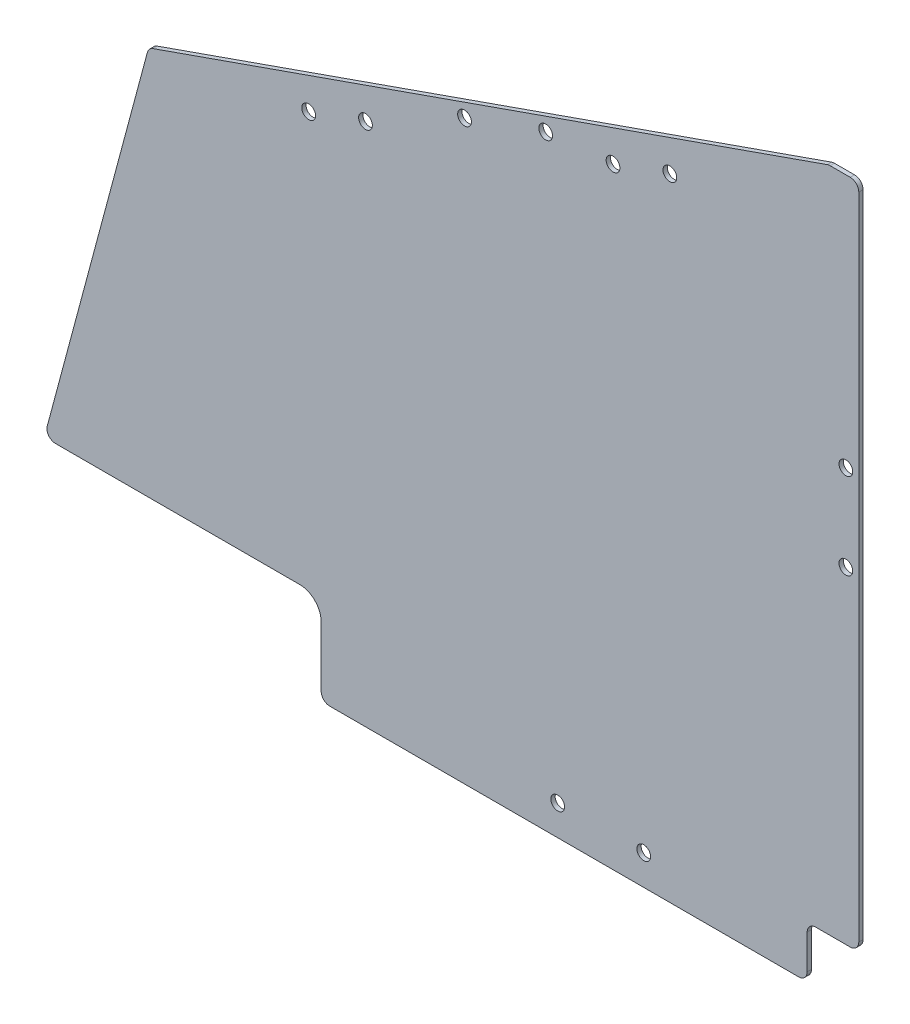
SolidWorks part; units mm, degrees
material "Thornel Mat VMA"
ref_plane "前视基准面" through (0, 0, 0) normal (0, 0, 1) x (1, 0, 0)
ref_plane "上视基准面" through (0, 0, 0) normal (0, 1, 0) x (1, 0, 0)
ref_plane "右视基准面" through (0, 0, 0) normal (1, 0, 0) x (0, 0, -1)
sketch "草图1" plane through (0, 0, 0) normal (0, 0, 1) x (1, 0, 0)
  line L1 (-95, -83.5) -> (95, -83.5)
  line L2 (-95, -83.5) -> (-95, 83.5)
  line L3 (-95, 83.5) -> (95, 83.5)
  line L4 (95, -83.5) -> (95, 83.5)
  line L5 (-95, -83.5) -> (95, 83.5) construction
  line L6 (-95, 83.5) -> (95, -83.5) construction
  point P0 (0, 0)
  dimension "D1" = 167
  dimension "D2" = 190
extrude "凸台-拉伸1" add sketch "草图1" along normal blind 1
sketch "草图2" plane through (0, 0, 0) normal (0, 0, -1) x (-1, 0, 0)
  line L0 (100, -83.5) -> (119, -83.5)
  line L1 (100, -83.5) -> (55.2525, 83.5)
  line L2 (-95, 83.5) -> (95, 83.5) construction
  line L3 (95, -83.5) -> (-95, -83.5) construction
  line L7 (119, -83.5) -> (119, 83.5)
  line L8 (119, 83.5) -> (55.2525, 83.5)
  dimension "D1" = 75
  dimension "D2" = 100
  dimension "D3" = 19
extrude "切除-拉伸1" cut sketch "草图2" against normal blind 1
sketch "草图3" plane through (0, 0, 0) normal (0, 0, -1) x (-1, 0, 0)
  line L0 (95, -83.5) -> (95, -62.5)
  line L1 (-95, -83.5) -> (-95, 83.5) construction
  line L3 (-88, 83.5) -> (55.2525, 83.5)
  line L4 (55.2525, 83.5) -> (95, -64.8397) construction
  line L5 (-88, 83.5) -> (70.1237, 28)
  line L6 (-95, 83.5) -> (55.2525, 83.5) construction
  line L7 (30, -83.5) -> (30, -62.5)
  line L8 (95, -83.5) -> (-95, -83.5) construction
  line L9 (30, -62.5) -> (95, -62.5)
  line L11 (95, -83.5) -> (30, -83.5)
  line L12 (55.2525, 83.5) -> (70.1237, 28)
  dimension "D1" = 28
  dimension "D2" = 7
  dimension "D3" = 21
  dimension "D4" = 30
extrude "切除-拉伸2" cut sketch "草图3" against normal blind 1
sketch "草图4" plane through (0, 0, 0) normal (0, 0, -1) x (-1, 0, 0)
  line L0 (0, 0) -> (-92, 0) construction
  line L1 (-92, 0) -> (-92, 4.5) construction
  line L2 (-92, 4.5) -> (-92, 24.5) construction
  line L3 (-95, -83.5) -> (-95, 83.5) construction
  circle A2 centre (-92, 4.5) radius 1.6
  circle A3 centre (-92, 24.5) radius 1.6
  dimension "D4" = 3.2
  dimension "D1" = 3
  dimension "D2" = 4.5
  dimension "D3" = 20
extrude "切除-拉伸3" cut sketch "草图4" against normal blind 1
sketch "草图9" plane through (0, 0, 0) normal (0, 0, -1) x (-1, 0, 0)
  circle A4 centre (-22.2058, 57.2274) radius 1.6
  circle A5 centre (-3.3344, 50.6037) radius 1.6
  dimension "D1" = 3.2
extrude "切除-拉伸5" cut sketch "草图9" against normal blind 10
fillet "圆角1" radius 5 1 edges at (-30, -62.5, 0.5)
fillet "圆角2" radius 2 6 edges at (95, 83.5, 0.5) (95, -83.5, 0.5) (-70.1237, 28, 0.5) (88, 83.5, 0.5) (-30, -83.5, 0.5) (-94.3731, -62.5, 0.5)
sketch "草图10" plane through (0, 0, 1) normal (0, 0, 1) x (1, 0, 0)
  line L0 (-28, -83.5) -> (93, -83.5) construction
  circle A1 centre (45, -76.5) radius 1.6
  circle A3 centre (25, -76.5) radius 1.6
  dimension "D2" = 3.2
  dimension "D1" = 20
  dimension "D3" = 7
  dimension "D4" = 25
extrude "切除-拉伸6" cut sketch "草图10" against normal blind 10
sketch "草图11" plane through (0, 0, 0) normal (0, 0, -1) x (-1, 0, 0)
  line L0 (-95, -71.5) -> (-83, -71.5)
  line L1 (-95, -81.5) -> (-95, 81.5) construction
  line L2 (-83, -71.5) -> (-83, -83.5)
  line L3 (28, -83.5) -> (-93, -83.5) construction
  line L4 (-83, -83.5) -> (-95, -83.5)
  line L5 (-95, -83.5) -> (-95, -71.5)
  dimension "D1" = 12
extrude "切除-拉伸7" cut sketch "草图11" against normal blind 10
fillet "圆角3" radius 2 3 edges at (83, -83.5, 0.5) (83, -71.5, 0.5) (95, -71.5, 0.5)
sketch "草图12" plane through (0, 0, 1) normal (0, 0, 1) x (1, 0, 0)
  circle A0 centre (-32.9067, 33.7501) radius 1.6
  circle A1 centre (-19.6968, 38.3867) radius 1.6
  circle A2 centre (37.8608, 58.5889) radius 1.6
  circle A3 centre (51.0707, 63.2255) radius 1.6
  dimension "D1" = 3.2
extrude "切除-拉伸8" cut sketch "草图12" against normal blind 10
